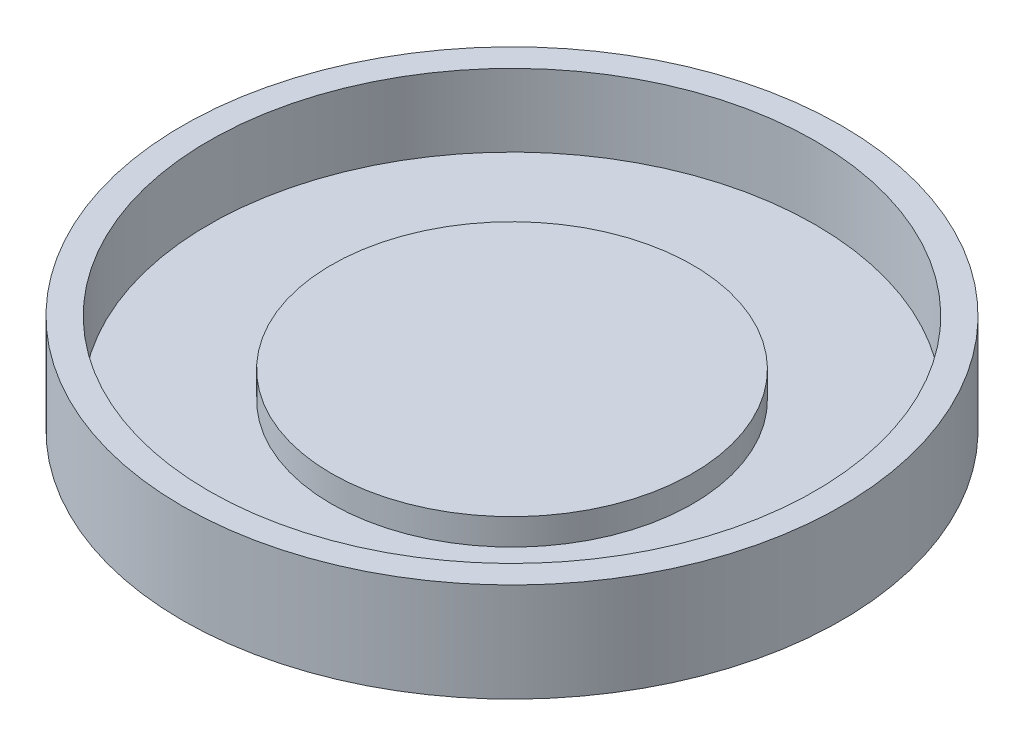
SolidWorks part; units mm, degrees
ref_plane "Front Plane" through (0, 0, 0) normal (0, 0, 1) x (1, 0, 0)
ref_plane "Top Plane" through (0, 0, 0) normal (0, 1, 0) x (1, 0, 0)
ref_plane "Right Plane" through (0, 0, 0) normal (1, 0, 0) x (0, 0, -1)
sketch "Sketch1" plane through (0, 0, 0) normal (0, 1, 0) x (1, 0, 0)
  circle A0 centre (0, 0) radius 50
  dimension "D1" = 100
extrude "Boss-Extrude2" add sketch "Sketch1" along normal blind 15
shell "Shell1" thickness 4
sketch "Sketch3" plane through (0, 4, 0) normal (0, 1, 0) x (1, 0, 0)
  circle A0 centre (0, 0) radius 27.405
  dimension "D1" = 54.81
extrude "Boss-Extrude3" add sketch "Sketch3" along normal blind 4
